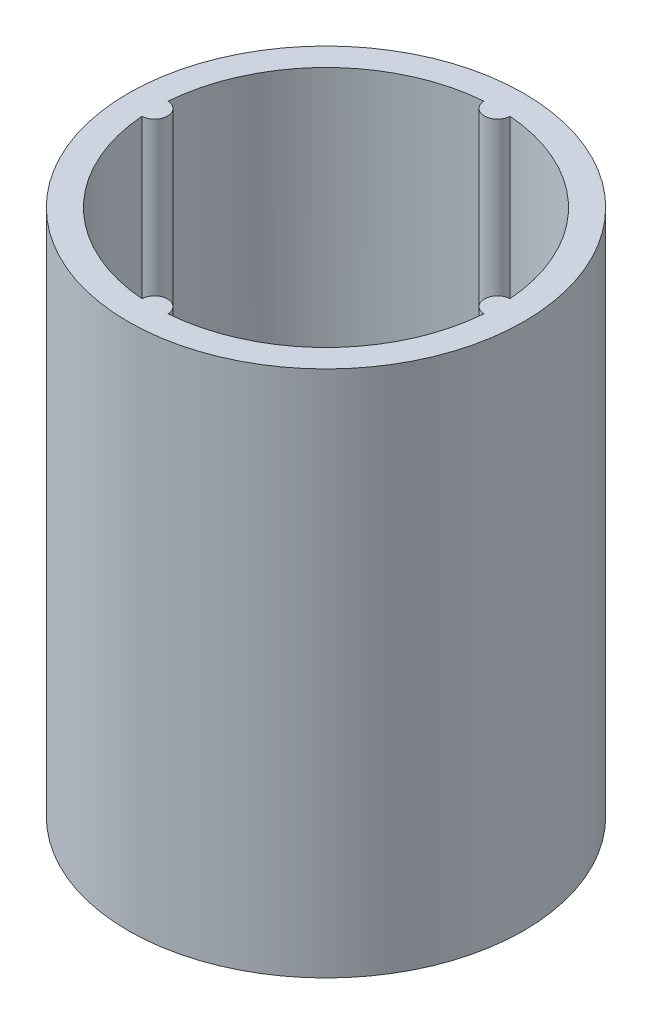
SolidWorks part; units mm, degrees
ref_plane "Front Plane" through (0, 0, 0) normal (0, 0, 1) x (1, 0, 0)
ref_plane "Top Plane" through (0, 0, 0) normal (0, 1, 0) x (1, 0, 0)
ref_plane "Right Plane" through (0, 0, 0) normal (1, 0, 0) x (0, 0, -1)
sketch "Sketch2" plane through (0, 0, 0) normal (0, 1, 0) x (1, 0, 0)
  circle A0 centre (0, 0) radius 30
  dimension "D1" = 60
extrude "Boss-Extrude1" add sketch "Sketch2" along normal blind 80
sketch "Sketch3" plane through (0, 80, 0) normal (0, 1, 0) x (1, 0, 0)
  circle A0 centre (0, 0) radius 26.0169
extrude "Cut-Extrude4" cut sketch "Sketch3" against normal blind 75 contours A0
sketch "Sketch5" plane through (0, 0, 0) normal (1, 0, 0) x (0, 0, -1)
  line L0 (-30, 80) -> (-30, 0) construction
  line L1 (-20, 11.1243) -> (20, 11.1243)
  line L2 (-20, 11.1243) -> (-20, 1.1243)
  line L3 (-20, 1.1243) -> (20, 1.1243)
  line L4 (20, 11.1243) -> (20, 1.1243)
  line L5 (-20, 11.1243) -> (20, 1.1243) construction
  line L6 (-20, 1.1243) -> (20, 11.1243) construction
  point P0 (0, 6.1243)
  dimension "D1" = 40
  dimension "D2" = 10
  dimension "D3" = 10
extrude "Cut-Extrude6" cut sketch "Sketch5" against normal through all
sketch "Sketch6" plane through (0, 80, 0) normal (0, 1, 0) x (1, 0, 0)
  circle A1 centre (26.0169, 0) radius 1.9831
  arc A2 (-16.6397, -20) -> (-16.6397, 20) centre (0, 0) ccw construction
  circle A3 centre (0, 0) radius 26.0169 construction
  circle A4 centre (-26.0169, 0) radius 1.9831
  circle A5 centre (0, -26.0169) radius 1.9831
  circle A6 centre (0, 26.0169) radius 1.9831
extrude "Boss-Extrude2" add sketch "Sketch6" against normal blind 63
